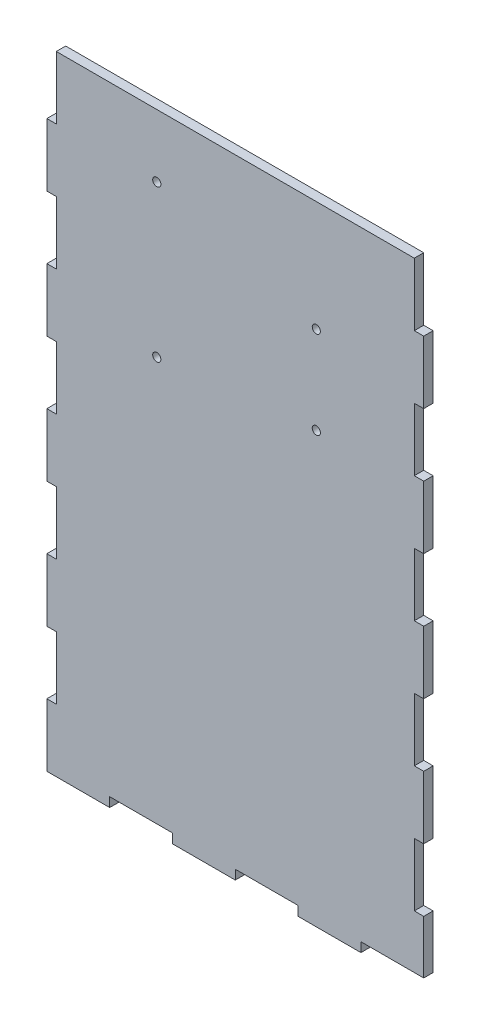
SolidWorks part; units mm, degrees
ref_plane "Front Plane" through (0, 0, 0) normal (0, 0, 1) x (1, 0, 0)
ref_plane "Top Plane" through (0, 0, 0) normal (0, 1, 0) x (1, 0, 0)
ref_plane "Right Plane" through (0, 0, 0) normal (1, 0, 0) x (0, 0, -1)
sketch "Sketch1" plane through (0, 0, 0) normal (0, 0, 1) x (1, 0, 0)
  line L1 (-170, -50) -> (-50, -50)
  line L2 (-170, -50) -> (-170, 150)
  line L3 (-170, 150) -> (-50, 150)
  line L4 (-50, -50) -> (-50, 150)
  line L41 (-50, 110) -> (-50, 90)
  circle A0 centre (-135, 130) radius 1.3
  circle A1 centre (-84.2, 114.8) radius 1.3
  circle A2 centre (-84.2, 86.9) radius 1.3
  circle A3 centre (-135, 81.7) radius 1.3
  dimension "D5" = 50.8
  dimension "D7" = 48.3
  dimension "D8" = 27.9
  dimension "D1" = 120
  dimension "D2" = 200
  dimension "D3" = 50
  dimension "D4" = 50
  dimension "D6" = 15.2
  dimension "D9" = 35
  dimension "D10" = 20
extrude "Boss-Extrude2" add sketch "Sketch1" along normal blind 3
sketch "Sketch4" plane through (-50, 0, 0) normal (1, 0, 0) x (0, 0, -1)
  line L0 (0, -50) -> (0, 150) construction
  line L1 (-3, 150) -> (0, 150)
  line L2 (-3, 150) -> (-3, 130)
  line L3 (-3, 130) -> (0, 130)
  line L4 (0, 150) -> (0, 130)
  line L6 (-3, 130) -> (0, 130)
  line L7 (-3, 130) -> (-3, 110)
  line L8 (-3, 110) -> (0, 110)
  line L9 (0, 130) -> (0, 110)
  line M2 (0, -50) -> (0, 150)
  line M3 (0, 150) -> (-3, 150)
  line M4 (-3, 150) -> (-3, -50)
  dimension "D1" = 20
  dimension "D2" = 20
extrude "Cut-Extrude1" cut sketch "Sketch4" against normal blind 3 contours L3 M4 M2 M3
sketch "Sketch5" plane through (-50, 0, 0) normal (1, 0, 0) x (0, 0, -1)
  line L0 (-3, -50) -> (-3, 130) construction
  line L1 (0, 130) -> (-3, 130)
  line L2 (0, 130) -> (0, 110)
  line L3 (0, 110) -> (-3, 110)
  line L4 (-3, 130) -> (-3, 110)
  line L5 (0, -50) -> (0, 130) construction
  line L6 (-3, 110) -> (0, 110)
  line L7 (-3, 110) -> (-3, 90)
  line L8 (-3, 90) -> (0, 90)
  line L9 (0, 110) -> (0, 90)
  line L11 (-3, 90) -> (0, 90)
  line L12 (-3, 90) -> (-3, 70)
  line L13 (-3, 70) -> (0, 70)
  line L14 (0, 90) -> (0, 70)
  line L15 (-3, 70) -> (0, 70)
  line L16 (-3, 70) -> (-3, 50)
  line L17 (-3, 50) -> (0, 50)
  line L18 (0, 70) -> (0, 50)
  line M4 (0, -50) -> (0, 130)
  line M6 (-3, 130) -> (-3, -50)
  dimension "D1" = 20
  dimension "D2" = 20
  dimension "D3" = 20
  dimension "D4" = 20
extrude "Cut-Extrude2" cut sketch "Sketch5" against normal blind 3 contours L8 L3 M6 M4
ref_plane "Plane1" through (-50, 90, 0) normal (0, 1, 0) x (1, 0, 0)
sketch "Sketch7" plane through (-50, 0, 0) normal (1, 0, 0) x (0, 0, -1)
  line L0 (0, -50) -> (0, 90) construction
  line L1 (-3, 90) -> (0, 90)
  line L2 (-3, 90) -> (-3, 70)
  line L3 (-3, 70) -> (0, 70)
  line L4 (0, 90) -> (0, 70)
  line L6 (-3, 70) -> (0, 70)
  line L7 (-3, 70) -> (-3, 50)
  line L8 (-3, 50) -> (0, 50)
  line L9 (0, 70) -> (0, 50)
  line L10 (-3, 50) -> (0, 50)
  line L11 (-3, 50) -> (-3, 30)
  line L12 (-3, 30) -> (0, 30)
  line L13 (0, 50) -> (0, 30)
  line M4 (0, -50) -> (0, 90)
  line M6 (-3, 90) -> (-3, -50)
  dimension "D1" = 20
  dimension "D2" = 20
  dimension "D3" = 20
extrude "Cut-Extrude3" cut sketch "Sketch7" against normal blind 3 contours L8 L3 M6 M4
sketch "Sketch8" plane through (-50, 0, 0) normal (1, 0, 0) x (0, 0, -1)
  line L0 (-3, -50) -> (-3, 50) construction
  line L1 (0, 50) -> (-3, 50)
  line L2 (0, 50) -> (0, 30)
  line L3 (0, 30) -> (-3, 30)
  line L4 (-3, 50) -> (-3, 30)
  line L5 (0, -50) -> (0, 50) construction
  line L6 (-3, 30) -> (0, 30)
  line L7 (-3, 30) -> (-3, 10)
  line L8 (-3, 10) -> (0, 10)
  line L9 (0, 30) -> (0, 10)
  line M3 (0, -50) -> (0, 50)
  line M5 (-3, 50) -> (-3, -50)
  dimension "D1" = 20
  dimension "D2" = 20
extrude "Cut-Extrude4" cut sketch "Sketch8" against normal blind 3 contours L8 L3 M5 M3
sketch "Sketch9" plane through (-50, 0, 0) normal (1, 0, 0) x (0, 0, -1)
  line L0 (0, -50) -> (0, 10) construction
  line L1 (-3, 10) -> (0, 10)
  line L2 (-3, 10) -> (-3, -10)
  line L3 (-3, -10) -> (0, -10)
  line L4 (0, 10) -> (0, -10)
  line L6 (-3, -10) -> (0, -10)
  line L7 (-3, -10) -> (-3, -30)
  line L8 (-3, -30) -> (0, -30)
  line L9 (0, -10) -> (0, -30)
  line M6 (0, -50) -> (0, 10)
  line M8 (-3, 10) -> (-3, -50)
  dimension "D1" = 20
  dimension "D2" = 20
extrude "Cut-Extrude5" cut sketch "Sketch9" against normal blind 3 contours L8 L3 M8 M6
sketch "Sketch11" plane through (-170, 0, 0) normal (-1, 0, 0) x (0, 0, 1)
  line L0 (3, -50) -> (3, 150) construction
  line L1 (0, 150) -> (3, 150)
  line L2 (0, 150) -> (0, 130)
  line L3 (0, 130) -> (3, 130)
  line L4 (3, 150) -> (3, 130)
  dimension "D1" = 20
extrude "Cut-Extrude7" cut sketch "Sketch11" against normal blind 3 contours L2 L1 L4 L3
sketch "Sketch12" plane through (-170, 0, 0) normal (-1, 0, 0) x (0, 0, 1)
  line L0 (0, 130) -> (3, 130) construction
  line L1 (3, 130) -> (0, 130)
  line L2 (3, 130) -> (3, 110)
  line L3 (3, 110) -> (0, 110)
  line L4 (0, 130) -> (0, 110)
  line L5 (3, -50) -> (3, 130) construction
  line L6 (0, -50) -> (0, 130) construction
  line L8 (3, 110) -> (0, 110)
  line L9 (3, 110) -> (3, 90)
  line L10 (3, 90) -> (0, 90)
  line L11 (0, 110) -> (0, 90)
  line M4 (0, 130) -> (0, -50)
  line M6 (3, -50) -> (3, 130)
  dimension "D1" = 20
  dimension "D2" = 20
extrude "Cut-Extrude8" cut sketch "Sketch12" against normal blind 3 contours L10 L3 M6 M4
sketch "Sketch13" plane through (-170, 0, 0) normal (-1, 0, 0) x (0, 0, 1)
  line L0 (0, -50) -> (0, 90) construction
  line L1 (3, 90) -> (0, 90)
  line L2 (3, 90) -> (3, 70)
  line L3 (3, 70) -> (0, 70)
  line L4 (0, 90) -> (0, 70)
  line L6 (3, 70) -> (0, 70)
  line L7 (3, 70) -> (3, 50)
  line L8 (3, 50) -> (0, 50)
  line L9 (0, 70) -> (0, 50)
  line M3 (3, -50) -> (3, 90)
  line M5 (0, 90) -> (0, -50)
  dimension "D1" = 20
  dimension "D2" = 20
extrude "Cut-Extrude9" cut sketch "Sketch13" against normal blind 3 contours L8 L3 M3 M5
sketch "Sketch14" plane through (-170, 0, 0) normal (-1, 0, 0) x (0, 0, 1)
  line L0 (0, -50) -> (0, 50) construction
  line L1 (3, 50) -> (0, 50)
  line L2 (3, 50) -> (3, 30)
  line L3 (3, 30) -> (0, 30)
  line L4 (0, 50) -> (0, 30)
  line L6 (3, 30) -> (0, 30)
  line L7 (3, 30) -> (3, 10)
  line L8 (3, 10) -> (0, 10)
  line L9 (0, 30) -> (0, 10)
  line M3 (3, -50) -> (3, 50)
  line M5 (0, 50) -> (0, -50)
  dimension "D1" = 20
  dimension "D2" = 20
extrude "Cut-Extrude10" cut sketch "Sketch14" against normal blind 3 contours L8 L3 M3 M5
sketch "Sketch15" plane through (-170, 0, 0) normal (-1, 0, 0) x (0, 0, 1)
  line L0 (0, -50) -> (0, 10) construction
  line L1 (3, 10) -> (0, 10)
  line L2 (3, 10) -> (3, -10)
  line L3 (3, -10) -> (0, -10)
  line L4 (0, 10) -> (0, -10)
  line L6 (3, -10) -> (0, -10)
  line L7 (3, -10) -> (3, -30)
  line L8 (3, -30) -> (0, -30)
  line L9 (0, -10) -> (0, -30)
  line M3 (3, -50) -> (3, 10)
  line M5 (0, 10) -> (0, -50)
  dimension "D1" = 20
  dimension "D2" = 20
extrude "Cut-Extrude11" cut sketch "Sketch15" against normal blind 3 contours L8 L3 M3 M5
sketch "Sketch16" plane through (0, -50, 0) normal (0, -1, 0) x (-1, 0, 0)
  line L0 (170, 0) -> (50, 0) construction
  line L1 (50, -3) -> (70, -3)
  line L2 (50, -3) -> (50, 0)
  line L3 (50, 0) -> (70, 0)
  line L4 (70, -3) -> (70, 0)
  dimension "D1" = 20
extrude "Cut-Extrude12" cut sketch "Sketch16" against normal blind 3 contours L2 L1 L4 L3
sketch "Sketch17" plane through (0, -50, 0) normal (0, -1, 0) x (-1, 0, 0)
  line L0 (170, 0) -> (70, 0) construction
  line L1 (70, -3) -> (90, -3)
  line L2 (70, -3) -> (70, 0)
  line L3 (70, 0) -> (90, 0)
  line L4 (90, -3) -> (90, 0)
  line L6 (90, -3) -> (110, -3)
  line L7 (90, -3) -> (90, 0)
  line L8 (90, 0) -> (110, 0)
  line L9 (110, -3) -> (110, 0)
  line M3 (170, 0) -> (70, 0)
  line M5 (70, -3) -> (170, -3)
  dimension "D1" = 20
  dimension "D2" = 20
extrude "Cut-Extrude13" cut sketch "Sketch17" against normal blind 3 contours L9 L4 M5 M3
sketch "Sketch19" plane through (0, -50, 0) normal (0, -1, 0) x (-1, 0, 0)
  line L0 (170, 0) -> (110, 0) construction
  line L1 (110, -3) -> (130, -3)
  line L2 (110, -3) -> (110, 0)
  line L3 (110, 0) -> (130, 0)
  line L4 (130, -3) -> (130, 0)
  line L5 (170, -3) -> (110, -3) construction
  line L6 (130, 0) -> (150, 0)
  line L7 (130, 0) -> (130, -3)
  line L8 (130, -3) -> (150, -3)
  line L9 (150, 0) -> (150, -3)
  line M3 (170, 0) -> (110, 0)
  line M5 (110, -3) -> (170, -3)
  dimension "D1" = 20
  dimension "D2" = 20
extrude "Cut-Extrude14" cut sketch "Sketch19" against normal blind 3 contours L9 L4 M3 M5
